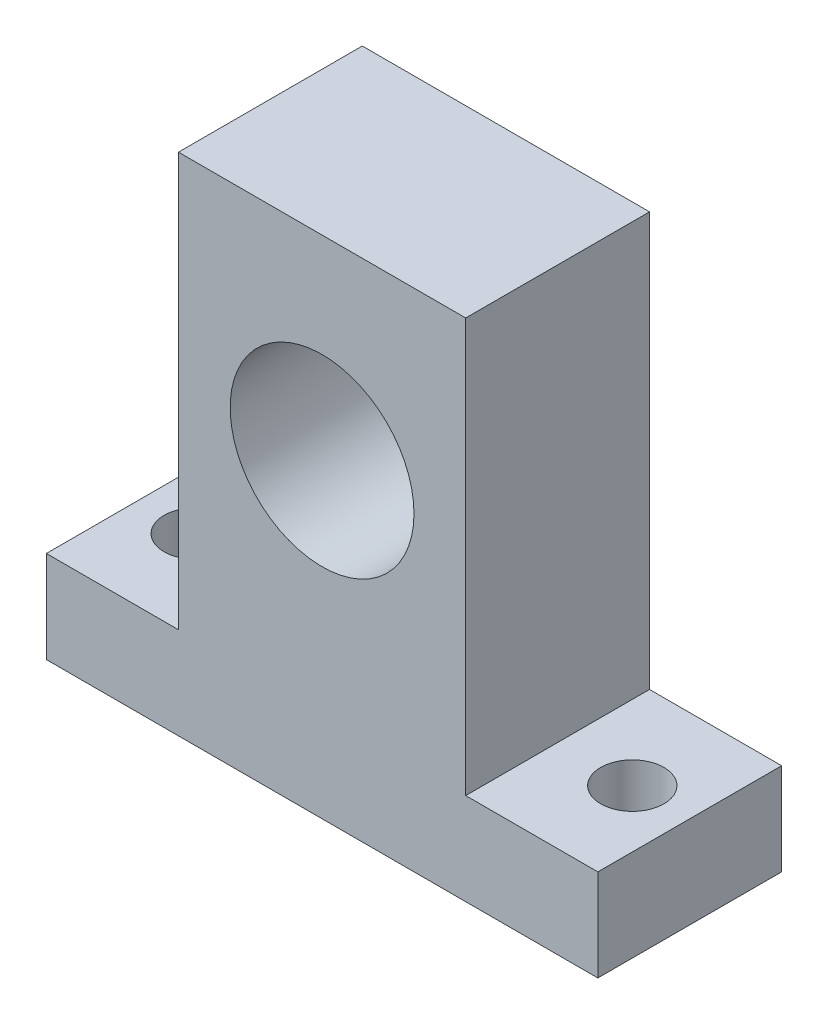
SolidWorks part; units mm, degrees
ref_plane "前视基准面" through (0, 0, 0) normal (0, 0, 1) x (1, 0, 0)
ref_plane "上视基准面" through (0, 0, 0) normal (0, 1, 0) x (1, 0, 0)
ref_plane "右视基准面" through (0, 0, 0) normal (1, 0, 0) x (0, 0, -1)
sketch "草图1" plane through (0, 0, 0) normal (0, 0, 1) x (1, 0, 0)
  line L0 (0, 62.3316) -> (0, -69.8918) construction
  line L1 (-24, 0) -> (24, 0)
  line L2 (24, 0) -> (24, 8)
  line L3 (24, 8) -> (12.5, 8)
  line L4 (12.5, 8) -> (12.5, 44)
  line L5 (12.5, 44) -> (-12.5, 44)
  line L6 (-24, 0) -> (-24, 8)
  line L7 (-24, 8) -> (-12.5, 8)
  line L8 (-12.5, 8) -> (-12.5, 44)
  circle A0 centre (0, 27) radius 8
  point P9 (0, 0)
  point P12 (0, 44)
  dimension "D5" = 16
  dimension "D1" = 44
  dimension "D2" = 48
  dimension "D3" = 25
  dimension "D4" = 8
  dimension "D6" = 27
extrude "凸台-拉伸1" add sketch "草图1" along normal mid plane 16
sketch "草图2" plane through (0, 8, 0) normal (0, 1, 0) x (1, 0, 0)
  line L0 (-25.3341, 0) -> (29.8145, 0) construction
  line L1 (0, 10.8063) -> (0, -12.4339) construction
  circle A0 centre (19, 0) radius 2.75
  circle A1 centre (-19, 0) radius 2.75
  dimension "D1" = 5.5
  dimension "D2" = 38
extrude "切除-拉伸1" cut sketch "草图2" against normal through all
